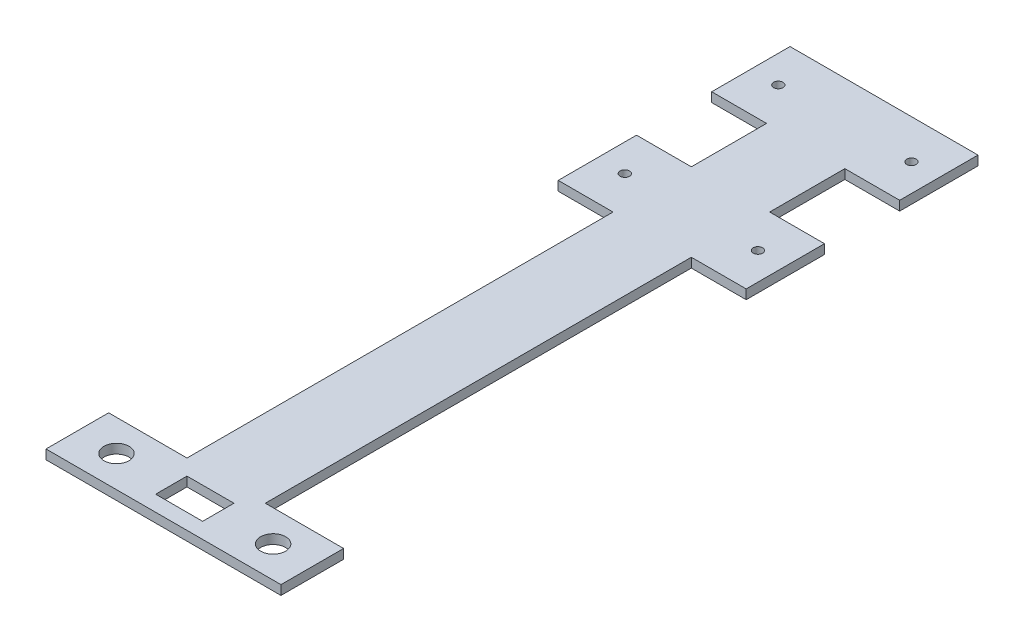
SolidWorks part; units mm, degrees
ref_plane "Front Plane" through (0, 0, 0) normal (0, 0, 1) x (1, 0, 0)
ref_plane "Top Plane" through (0, 0, 0) normal (0, 1, 0) x (1, 0, 0)
ref_plane "Right Plane" through (0, 0, 0) normal (1, 0, 0) x (0, 0, -1)
sketch "Sketch1" plane through (0, 0, 0) normal (0, 1, 0) x (1, 0, 0)
  line L0 (12.5, 66) -> (30, 66)
  line L1 (-12.5, -115) -> (12.5, -115)
  line L2 (-12.5, -115) -> (-12.5, 115)
  line L3 (-12.5, 115) -> (12.5, 115)
  line L4 (12.5, -115) -> (12.5, 115)
  line L5 (-12.5, -115) -> (12.5, 115) construction
  line L6 (-12.5, 115) -> (12.5, -115) construction
  line L7 (30, 66) -> (30, 41)
  line L8 (30, 41) -> (12.5, 41)
  line L9 (0, -115) -> (0, 115) construction
  line L10 (-30, 41) -> (-12.5, 41)
  line L11 (-30, 66) -> (-30, 41)
  line L12 (-12.5, 66) -> (-30, 66)
  line L13 (12.5, 90) -> (30, 90)
  line L14 (30, 90) -> (30, 115)
  line L15 (30, 115) -> (12.5, 115)
  line L16 (-30, 115) -> (-12.5, 115)
  line L17 (-30, 90) -> (-30, 115)
  line L18 (-12.5, 90) -> (-30, 90)
  line L19 (-12.5, -115) -> (-37.5, -115)
  line L20 (-37.5, -115) -> (-37.5, -95)
  line L21 (-37.5, -95) -> (-12.5, -95)
  line L22 (12.5, -115) -> (37.5, -115)
  line L23 (37.5, -115) -> (37.5, -95)
  line L24 (37.5, -95) -> (12.5, -95)
  point P0 (0, 0)
  dimension "D1" = 230
  dimension "D2" = 25
  dimension "D3" = 60
  dimension "D4" = 25
  dimension "D5" = 0
  dimension "D6" = 24
  dimension "D7" = 25
  dimension "D8" = 20
  dimension "D9" = 25
extrude "Boss-Extrude1" add sketch "Sketch1" along normal blind 3 contours L8 L7 L0 L4 | L1 L4 L3 L2 | L2 L12 L11 L10 | L14 L15 L4 L13 | L18 L2 L16 L17 | L21 L20 L19 L2 | L23 L24 L4 L22
sketch "Sketch2" plane through (0, 3, 0) normal (0, 1, 0) x (1, 0, 0)
  line L0 (30, 102.5) -> (-30, 102.5) construction
  line L3 (30, 90) -> (30, 115) construction
  line L6 (0, 0) -> (0, -115) construction
  line L7 (-30, 90) -> (-30, 115) construction
  line L8 (0, 115) -> (0, -115) construction
  line L9 (-37.5, -115) -> (37.5, -115) construction
  line L10 (-30, 115) -> (30, 115) construction
  line L11 (-30, 53.5) -> (30, 53.5) construction
  line L12 (-30, 66) -> (-30, 41) construction
  line L15 (30, 66) -> (30, 41) construction
  circle A0 centre (-21.25, 102.5) radius 1.5
  circle A1 centre (21.25, 102.5) radius 1.5
  circle A2 centre (-21.25, 53.5) radius 1.5
  circle A4 centre (21.25, 53.5) radius 1.5
  point P6 (0, 0)
  dimension "D1" = 3
  dimension "D2" = 42.5
  dimension "D3" = 42.5
  dimension "D4" = 3
extrude "Cut-Extrude1" cut sketch "Sketch2" against normal through all both and the other way through all
sketch "Sketch3" plane through (0, 3, 0) normal (0, 1, 0) x (1, 0, 0)
  line L0 (-37.5, -105) -> (37.5, -105) construction
  line L1 (-37.5, -115) -> (-37.5, -95) construction
  line L2 (37.5, -115) -> (37.5, -95) construction
  line L3 (0, -115) -> (0, 0) construction
  line L4 (-37.5, -115) -> (37.5, -115) construction
  line L6 (-7.5, -110) -> (7.5, -110)
  line L7 (-7.5, -110) -> (-7.5, -100)
  line L8 (-7.5, -100) -> (7.5, -100)
  line L9 (7.5, -110) -> (7.5, -100)
  line L10 (-7.5, -110) -> (7.5, -100) construction
  line L11 (-7.5, -100) -> (7.5, -110) construction
  circle A0 centre (-25, -105) radius 4
  circle A1 centre (25, -105) radius 4
  point P11 (0, -105)
  dimension "D3" = 8
  dimension "D4" = 50
  dimension "D1" = 15
  dimension "D2" = 10
extrude "Cut-Extrude2" cut sketch "Sketch3" against normal through all both and the other way through all
